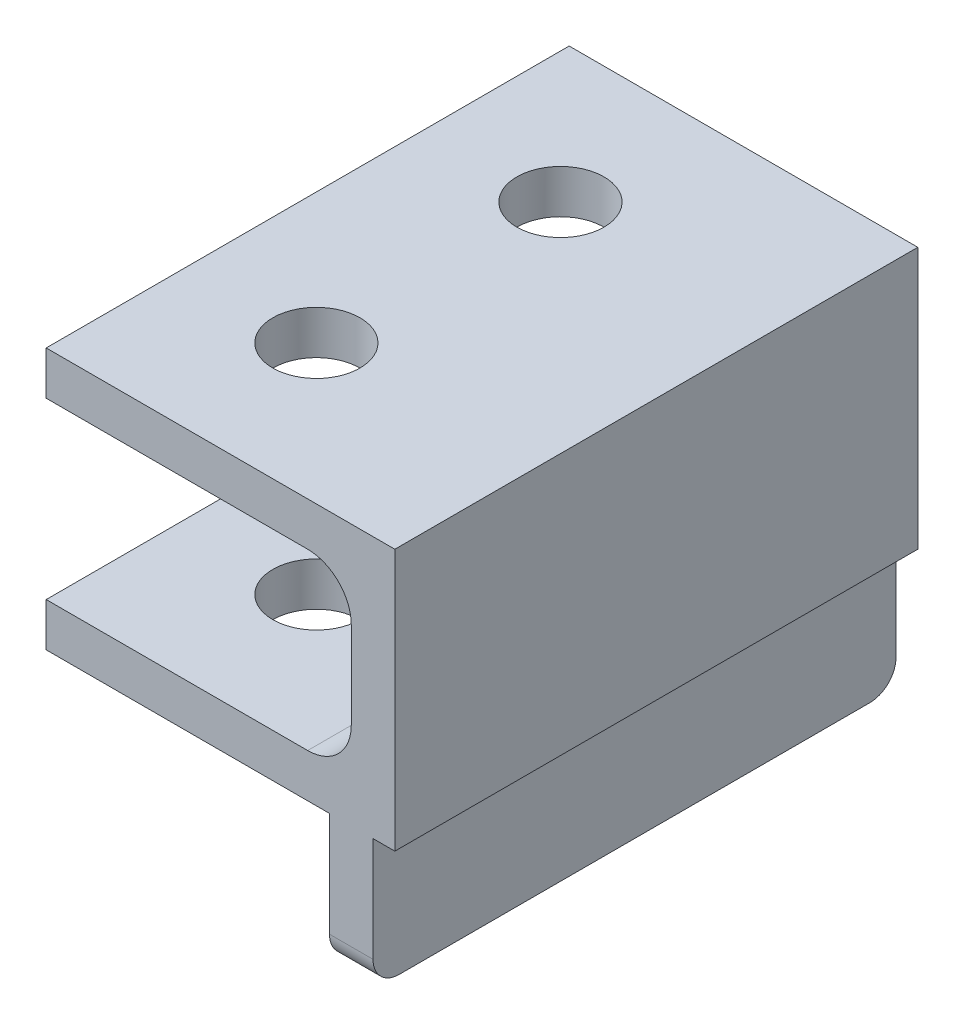
SolidWorks part; units mm, degrees
ref_plane "Front Plane" through (0, 0, 0) normal (0, 0, 1) x (1, 0, 0)
ref_plane "Top Plane" through (0, 0, 0) normal (0, 1, 0) x (1, 0, 0)
ref_plane "Right Plane" through (0, 0, 0) normal (1, 0, 0) x (0, 0, -1)
sketch "Sketch1" plane through (0, 0, 0) normal (0, 0, 1) x (1, 0, 0)
  line L0 (0, 0) -> (35, 0)
  line L1 (35, 0) -> (35, -20)
  line L2 (35, -20) -> (0, -20)
  line L3 (0, -20) -> (0, -25)
  line L4 (0, -25) -> (40, -25)
  line L5 (40, -25) -> (40, 5)
  line L6 (40, 5) -> (0, 5)
  line L7 (0, 5) -> (0, 0)
  dimension "D1" = 5
  dimension "D2" = 5
  dimension "D3" = 5
  dimension "D4" = 35
  dimension "D5" = 20
extrude "Boss-Extrude1" add sketch "Sketch1" along normal blind 60
fillet "Fillet1" radius 5 2 edges at (35, -20, 30) (35, 0, 30)
sketch "Sketch2" plane through (0, 5, 0) normal (0, 1, 0) x (1, 0, 0)
  line L0 (0, -30) -> (40, -30) construction
  line L1 (0, -60) -> (0, 0) construction
  line L2 (40, -60) -> (40, 0) construction
  circle A0 centre (15, -44) radius 5
  circle A2 centre (15, -16) radius 5
  dimension "D1" = 14
  dimension "D2" = 10
  dimension "D3" = 15
extrude "Cut-Extrude1" cut sketch "Sketch2" against normal blind 75 contours A0 | A2
sketch "Sketch3" plane through (0, -25, 0) normal (0, -1, 0) x (1, 0, 0)
  line L0 (0, 0) -> (40, 0) construction
  line L2 (32.5, 0) -> (32.5, 60)
  line L4 (37.5, 0) -> (37.5, 60)
  line L5 (0, 60) -> (40, 60) construction
  line L6 (40, 60) -> (40, 0) construction
  line L7 (32.5, 0) -> (37.5, 0)
  line L9 (37.5, 0) -> (37.5, 60)
  line L13 (32.5, 0) -> (32.5, 60)
  line L16 (32.5, 60) -> (37.5, 60)
  line M10 (0, 0) -> (40, 0)
  line M12 (40, 60) -> (0, 60)
  dimension "D1" = 5
  dimension "D2" = 2.5
extrude "Boss-Extrude2" add sketch "Sketch3" along normal blind 15 contours L4 L2 M10 M12
fillet "Fillet3" radius 3 2 edges at (35, -40, 0) (35, -40, 60)
